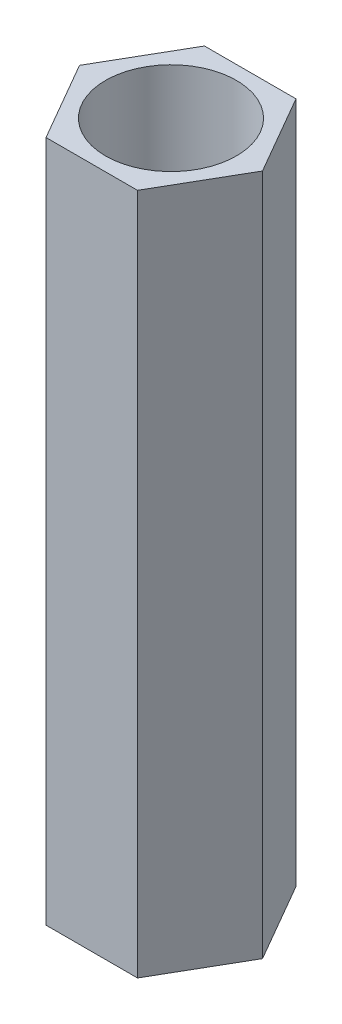
SolidWorks part; units mm, degrees
ref_plane "Front Plane" through (0, 0, 0) normal (0, 0, 1) x (1, 0, 0)
ref_plane "Top Plane" through (0, 0, 0) normal (0, 1, 0) x (1, 0, 0)
ref_plane "Right Plane" through (0, 0, 0) normal (1, 0, 0) x (0, 0, -1)
sketch "Sketch1" plane through (0, 0, 0) normal (0, 1, 0) x (1, 0, 0)
  line L1 (-1.6864, 0) -> (-0.8432, -1.4605)
  line L2 (-0.8432, -1.4605) -> (0.8432, -1.4605)
  line L3 (0.8432, -1.4605) -> (1.6864, 0)
  line L4 (1.6864, 0) -> (0.8432, 1.4605)
  line L5 (0.8432, 1.4605) -> (-0.8432, 1.4605)
  line L6 (-0.8432, 1.4605) -> (-1.6864, 0)
  circle A0 centre (0, 0) radius 1.4605 construction
  dimension "D1" = 2.921
extrude "Boss-Extrude1" add sketch "Sketch1" along normal blind 12.573
sketch "Sketch2" plane through (0, 12.573, 0) normal (0, 1, 0) x (1, 0, 0)
  circle A0 centre (0, 0) radius 1.2065
  dimension "D1" = 2.413
extrude "Cut-Extrude1" cut sketch "Sketch2" against normal through all
